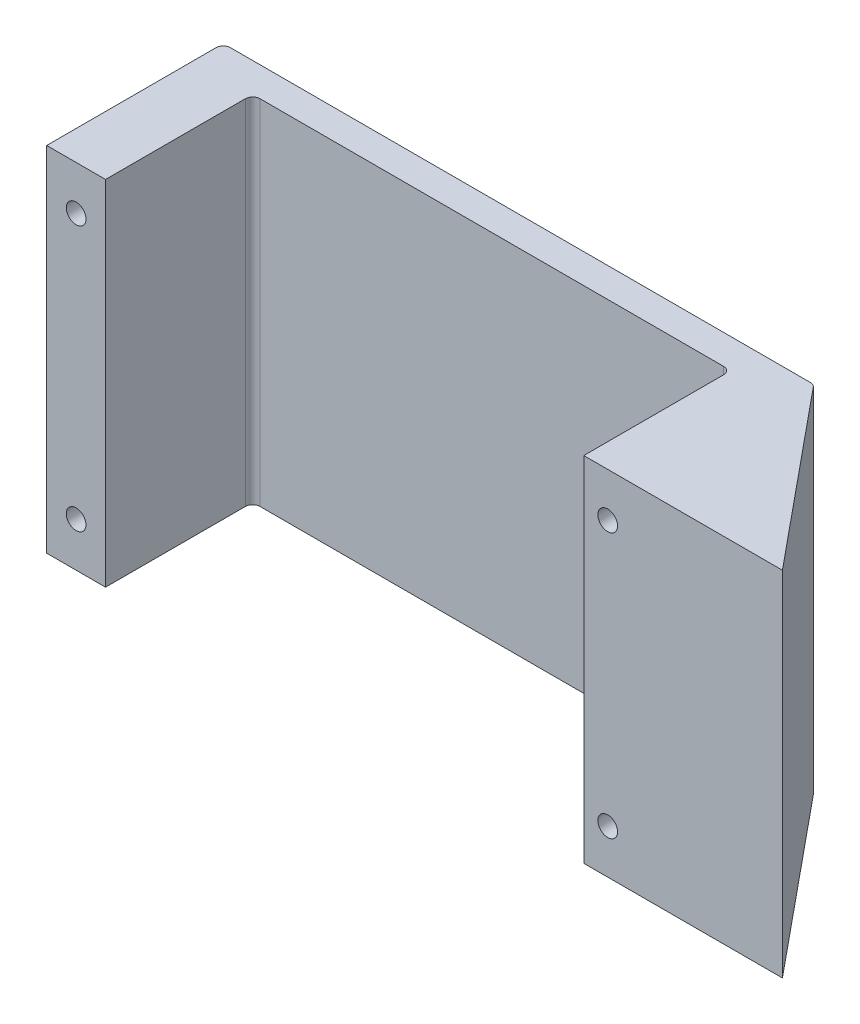
SolidWorks part; units mm, degrees
ref_plane "Front Plane" through (0, 0, 0) normal (0, 0, 1) x (1, 0, 0)
ref_plane "Top Plane" through (0, 0, 0) normal (0, 1, 0) x (1, 0, 0)
ref_plane "Right Plane" through (0, 0, 0) normal (1, 0, 0) x (0, 0, -1)
sketch "Sketch1" plane through (0, 0, 0) normal (0, 1, 0) x (1, 0, 0)
  line L10 (64.0121, -76.9792) -> (-62.9879, -76.9792) construction
  line L14 (-52.8279, -76.9792) -> (-62.9879, -76.9792)
  line L15 (29.7221, -76.9792) -> (64.0121, -76.9792)
  line L16 (64.0121, -76.9792) -> (38.9403, -46.4992)
  line L17 (-52.8279, -76.9792) -> (-52.8279, -51.5792)
  line L18 (-52.8279, -51.5792) -> (29.7221, -51.5792)
  line L19 (29.7221, -51.5792) -> (29.7221, -76.9792)
  line L20 (38.9403, -46.4992) -> (-62.9879, -46.4992)
  line L21 (-62.9879, -46.4992) -> (-62.9879, -76.9792)
  point P0 (0, 0)
  dimension "D3" = 10.16
  dimension "D4" = 34.29
extrude "Boss-Extrude1" add sketch "Sketch1" along normal blind 20.32 and the other way blind 40.64
sketch "Sketch3" plane through (0, 0, 46.4992) normal (0, 0, -1) x (-1, 0, 0)
  line L0 (62.9879, -40.64) -> (62.9879, 20.32) construction
  line L1 (62.9879, 20.32) -> (-38.9403, 20.32) construction
  line L2 (-38.9403, 20.32) -> (-38.9403, -40.64) construction
  line L3 (-38.9403, -40.64) -> (62.9879, -40.64) construction
  line L4 (62.9879, -40.64) -> (52.8279, -40.64) construction
  line L5 (52.8279, -40.64) -> (52.8279, 20.32) construction
  line L6 (52.8279, 20.32) -> (62.9879, 20.32) construction
  line L7 (52.8279, -40.64) -> (52.8279, -33.02) construction
  line L8 (52.8279, -33.02) -> (62.9879, -33.02) construction
  line L9 (52.8279, 20.32) -> (52.8279, 12.7) construction
  line L10 (52.8279, 12.7) -> (62.9879, 12.7) construction
  line L11 (52.8279, -33.02) -> (-38.9403, -33.02) construction
  line L12 (52.8279, 12.7) -> (-28.7803, 12.7) construction
  line L13 (-38.9403, -40.64) -> (-28.7803, -40.64) construction
  line L14 (-28.7803, -40.64) -> (-28.7803, 20.32) construction
  line L15 (-28.7803, 12.7) -> (-38.9403, 12.7) construction
  point P11 (57.9079, -33.02)
  point P14 (57.9079, 12.7)
  point P18 (-33.8603, 12.7)
  point P23 (-33.8603, -33.02)
  dimension "D1" = 7.62
  dimension "D2" = 7.62
  dimension "D3" = 10.16
hole_wizard "CBORE for M3 Pan Head Machine Screw1" positions "Sketch3" profile "Sketch4" counterbore size "M3" standard "ANSI Metric" end condition through all
sketch "Sketch4" plane through (33.8603, -33.02, 46.4992) normal (1, 0, 0) x (0, 1, 0)
  line L0 (0, 0) -> (0, 30.48)
  line L1 (0, 30.48) -> (1.7, 30.48)
  line L3 (1.7, 30.48) -> (1.7, 2.4)
  line L4 (3.5, 2.4) -> (1.7, 2.4)
  line L5 (3.5, 2.4) -> (3.5, 0.025)
  line L6 (3.5, 0.025) -> (3.525, 0)
  line L7 (3.525, 0) -> (0, 0)
  line L8 (-3.5, 0.025) -> (-3.525, 0) construction
  line L11 (0, -6.35) -> (0, 107.95) construction
  dimension "Thru Hole Dia." = 3.4
  dimension "Thru Hole Depth" = 30.48
  dimension "C'Bore Dia." = 7
  dimension "C'Bore Depth" = 2.4
  dimension "Near C'Sink Dia." = 7.05
  dimension "Near C'Sink Angle" = 90
fillet "Fillet1" radius 1.27 4 edges at (29.7221, -10.16, 51.5792) (-52.8279, -10.16, 51.5792) (38.9403, -10.16, 46.4992) (-62.9879, -10.16, 46.4992)
